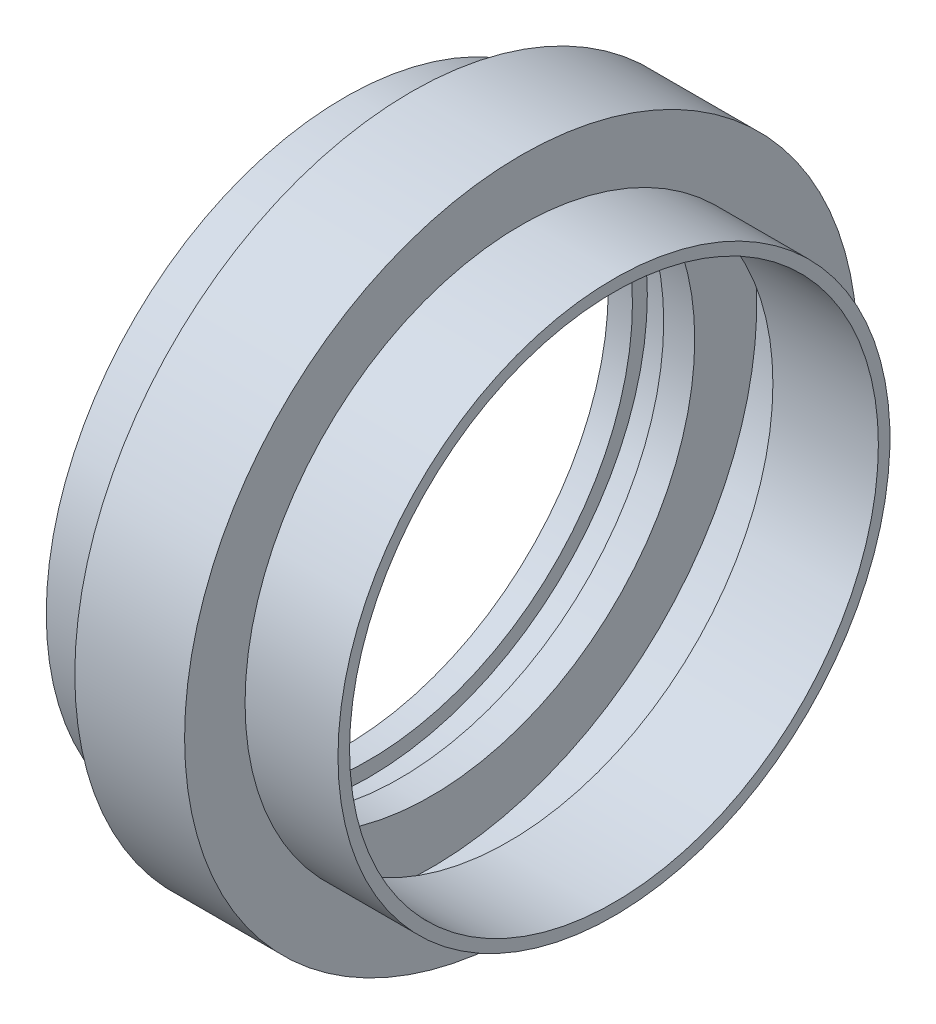
SolidWorks part; units mm, degrees
ref_plane "Front Plane" through (0, 0, 0) normal (0, 0, 1) x (1, 0, 0)
ref_plane "Top Plane" through (0, 0, 0) normal (0, 1, 0) x (1, 0, 0)
ref_plane "Right Plane" through (0, 0, 0) normal (1, 0, 0) x (0, 0, -1)
sketch "Sketch1" plane through (0, 0, 0) normal (0, 0, 1) x (1, 0, 0)
  line L0 (0, 0) -> (0, 3.048)
  line L1 (0, 3.048) -> (6.4, 3.048)
  line L2 (6.4, 3.048) -> (6.4, 0)
  line L3 (6.4, 0) -> (12.75, 0)
  line L4 (12.75, 0) -> (12.75, 12.7)
  line L5 (12.75, 12.7) -> (28.625, 12.7)
  line L6 (28.625, 12.7) -> (28.625, 0.127)
  line L7 (28.625, 0.127) -> (50.215, 0.127)
  line L11 (8.0909, -54) -> (50008.0909, -54) construction
  line L12 (0, 0) -> (-4.9524, 0)
  line L13 (-4.9524, 0) -> (-4.9524, 7.0451)
  line L15 (-4.9524, 7.0451) -> (8.7161, 7.0451)
  line L16 (8.7161, 7.0451) -> (8.7161, 14.8713)
  line L17 (8.7161, 14.8713) -> (31.1926, 14.8713)
  line L18 (31.1926, 14.8713) -> (31.1926, 2.4957)
  line L24 (50.215, 0.127) -> (50.215, 2.4957)
  line L25 (50.215, 2.4957) -> (31.1926, 2.4957)
  point P15 (31.1926, 2.7364)
  dimension "D1" = 3.048
  dimension "D2" = 6.4
  dimension "D3" = 3.048
  dimension "D4" = 6.35
  dimension "D5" = 15.875
  dimension "D6" = 21.59
  dimension "D7" = 12.7
  dimension "D8" = 12.573
  dimension "D9" = 54
revolve "Revolve5" add sketch "Sketch1" angle 360 about L11
